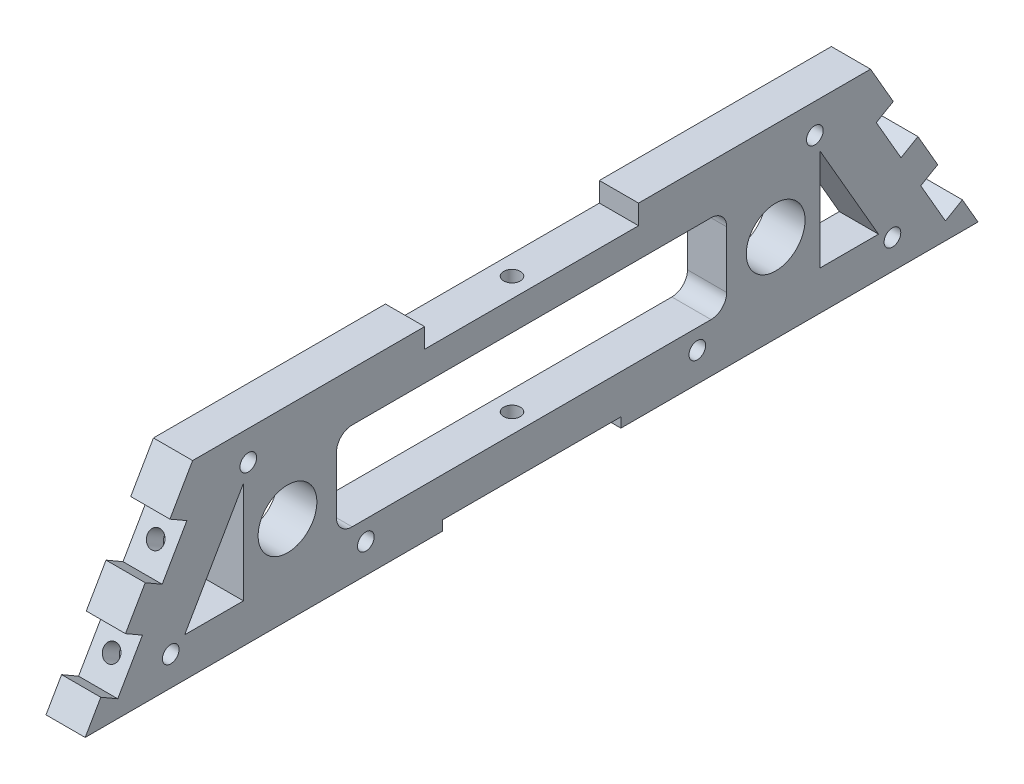
SolidWorks part; units mm, degrees
material "6061-T6 (SS)"
ref_plane "Front Plane" through (0, 0, 0) normal (0, 0, 1) x (1, 0, 0)
ref_plane "Top Plane" through (0, 0, 0) normal (0, 1, 0) x (1, 0, 0)
ref_plane "Right Plane" through (0, 0, 0) normal (1, 0, 0) x (0, 0, -1)
sketch "Sketch1" plane through (0, 0, 0) normal (1, 0, 0) x (0, 0, -1)
  line L0 (0, 0) -> (-17.4143, 30.1625)
  line L1 (-57.8739, 1.5875) -> (-86.8299, 1.5875)
  line L3 (-55.0164, 26.9875) -> (-89.6874, 26.9875)
  line L4 (-127.2895, 30.1625) -> (-89.6874, 30.1625)
  line L5 (-144.7038, 0) -> (-127.2895, 30.1625)
  line L6 (-17.4143, 30.1625) -> (-55.0164, 30.1625)
  line L7 (-55.0164, 30.1625) -> (-55.0164, 26.9875)
  line L8 (-89.6874, 30.1625) -> (-89.6874, 26.9875)
  line L9 (0, 0) -> (-57.8739, 0)
  line L10 (-57.8739, 0) -> (-57.8739, 1.5875)
  line L12 (-144.7038, 0) -> (-86.8299, 0)
  line L13 (-86.8299, 0) -> (-86.8299, 1.5875)
  circle A0 centre (-111.9124, 14.2875) radius 4.7625
  circle A1 centre (-32.7914, 14.2875) radius 4.7625
  dimension "D3" = 9.525
  dimension "D5" = 9.525
  dimension "D9" = 60
  dimension "D12" = 22.225
  dimension "D6" = 79.121
  dimension "D7" = 12.7
  dimension "D11" = 14.2875
  dimension "D14" = 22.225
  dimension "D15" = 15.875
  dimension "D19" = 32.7914
  dimension "D2" = 14.2875
  dimension "D4" = 12.7
  dimension "D8" = 12.7
  dimension "D10" = 60
  dimension "D13" = 15.875
  dimension "D16" = 25.0825
  dimension "D17" = 25.0825
  dimension "D18" = 32.7914
extrude "Boss-Extrude1" add sketch "Sketch1" along normal blind 6.35
hole_wizard "Tap Drill for #6-32 Tap2" positions "Sketch15" profile "Sketch14" hole size "#6-32" standard "ANSI Inch"
sketch "Sketch15" plane through (0, 62.6586, 108.5278) normal (0, 0.5, 0.866) x (1, 0, 0)
  line L5 (6.35, -37.5232) -> (0, -37.5232) construction
  point P3 (3.175, -62.9232)
  point P16 (3.175, -48.6357)
  dimension "D1" = 25.4
  dimension "D2" = 11.1125
sketch "Sketch14" plane through (3.175, 8.1655, 139.9895) normal (1, 0, 0) x (0, -0.866, 0.5)
  line L0 (0, 0) -> (0, 7.1627)
  line L1 (0, 7.1627) -> (1.3525, 6.35)
  line L2 (1.3525, 6.35) -> (1.3525, 0)
  line L5 (1.3525, 0) -> (0, 0)
  line L10 (0, 7.1627) -> (-1.3525, 6.35) construction
  line L11 (0, -6.35) -> (0, 107.95) construction
  dimension "Hole Dia." = 2.7051
  dimension "Hole Depth" = 6.35
  dimension "Drill Angle" = 118
sketch "Sketch18" plane through (0, 0, 0) normal (-1, 0, 0) x (0, 0, 1)
  line L0 (16.1226, 6.35) -> (25.6476, 6.35)
  line L1 (40.7289, 22.225) -> (103.9749, 22.225)
  line L2 (40.7289, 22.225) -> (40.7289, 7.9375)
  line L3 (40.7289, 7.9375) -> (103.9749, 7.9375)
  line L4 (103.9749, 22.225) -> (103.9749, 7.9375)
  line L5 (25.6476, 6.35) -> (25.6476, 22.8478)
  line L6 (127.2895, 30.1625) -> (89.6874, 30.1625) construction
  line L7 (16.1226, 6.35) -> (25.6476, 22.8478)
  line L8 (0, 0) -> (57.8739, 0) construction
  line L10 (0, 0) -> (17.4143, 30.1625) construction
  line L11 (72.3519, 26.9875) -> (72.3519, -9.7243) construction
  line L12 (55.0164, 26.9875) -> (89.6874, 26.9875) construction
  line L13 (119.0562, 6.35) -> (119.0562, 22.8478)
  line L14 (128.5812, 6.35) -> (119.0562, 22.8478)
  line L15 (128.5812, 6.35) -> (119.0562, 6.35)
  circle A0 centre (32.7914, 14.2875) radius 4.7625 construction
  circle A2 centre (111.9124, 14.2875) radius 4.7625 construction
  circle A3 centre (32.7914, 14.2875) radius 4.7625 construction
  dimension "D2" = 7.9375
  dimension "D1" = 7.9375
  dimension "D3" = 7.9375
  dimension "D4" = 22.225
  dimension "D5" = 7.1437
  dimension "D6" = 6.35
  dimension "D7" = 9.525
extrude "Cut-Extrude1" cut sketch "Sketch18" against normal through all
fillet "Fillet1" radius 2.54 4 edges at (3.175, 7.9375, 40.7289) (3.175, 22.225, 40.7289) (3.175, 7.9375, 103.9749) (3.175, 22.225, 103.9749)
hole_wizard "Tap Drill for #6-32 Tap4" positions "Sketch22" profile "Sketch21" hole size "#6-32" standard "ANSI Inch" end condition through all
sketch "Sketch22" plane through (0, 26.9875, 0) normal (0, 1, 0) x (1, 0, 0)
  line L0 (6.35, -55.0164) -> (6.35, -89.6874) construction
  line L1 (6.35, -89.6874) -> (0, -89.6874) construction
  point P0 (3.175, -72.3519)
  point P4 (6.35, -72.3519)
  point P7 (3.175, -89.6874)
sketch "Sketch21" plane through (3.175, 26.9875, 72.3519) normal (1, 0, 0) x (0, 0, 1)
  line L0 (0, 0) -> (0, 26.9875)
  line L1 (0, 26.9875) -> (1.3525, 26.9875)
  line L2 (1.3525, 26.9875) -> (1.3525, 0)
  line L5 (1.3525, 0) -> (0, 0)
  line L11 (0, -6.35) -> (0, 107.95) construction
  dimension "Thru Hole Dia." = 2.7051
  dimension "Thru Hole Depth" = 26.9875
ref_plane "Plane1" through (0, 0, 72.3519) normal (0, 0, -1) x (-1, 0, 0)
mirror "Mirror1" about plane through (0, 0, 72.3519) normal (0, 0, -1) of "Tap Drill for #6-32 Tap2"
hole_wizard "Tap Drill for #6-32 Tap1" positions "Sketch13" profile "Sketch12" hole size "#6-32" standard "ANSI Inch"
sketch "Sketch13" plane through (6.35, 15.8955, 9.3658) normal (1, 0, 0) x (0, 0, -1)
  circle A0 centre (-102.5466, -1.608) radius 4.7625 construction
  circle A1 centre (-102.5466, -1.608) radius 4.7625 construction
  point P24 (-108.8966, 9.5045)
  point P58 (-89.8466, -11.133)
  point P62 (-121.4696, -11.133)
  dimension "D1" = 11.1125
  dimension "D4" = 6.35
  dimension "D7" = 12.7
  dimension "D8" = 9.525
  dimension "D9" = 18.923
  dimension "D10" = 9.525
sketch "Sketch12" plane through (6.35, 25.4, 118.2624) normal (0, 1, 0) x (0, 0, -1)
  line L0 (0, 0) -> (0, 7.1627)
  line L1 (0, 7.1627) -> (1.3525, 6.35)
  line L2 (1.3525, 6.35) -> (1.3525, 0)
  line L5 (1.3525, 0) -> (0, 0)
  line L10 (0, 7.1627) -> (-1.3525, 6.35) construction
  line L11 (0, -6.35) -> (0, 107.95) construction
  dimension "Hole Dia." = 2.7051
  dimension "Hole Depth" = 6.35
  dimension "Drill Angle" = 118
mirror "Mirror2" about plane through (0, 0, 72.3519) normal (0, 0, -1) of "Tap Drill for #6-32 Tap1"
sketch "Sketch23" plane through (0, 0, 0) normal (0, 0.5, -0.866) x (-1, 0, 0)
  line L0 (-6.35, 0) -> (-6.35, 5.0578) construction
  line L1 (-6.35, 27.4606) -> (0, 27.4606)
  line L2 (-6.35, 27.4606) -> (-6.35, 19.4596)
  line L3 (-6.35, 19.4596) -> (0, 19.4596)
  line L4 (0, 27.4606) -> (0, 19.4596)
  line L5 (0, 0) -> (0, 5.0578) construction
  line L7 (0, 13.0588) -> (-6.35, 13.0588)
  line L8 (0, 13.0588) -> (0, 5.0578)
  line L9 (0, 5.0578) -> (-6.35, 5.0578)
  line L10 (-6.35, 13.0588) -> (-6.35, 5.0578)
  line L16 (-6.1722, 27.4606) -> (-6.1722, 32.2231)
  line L17 (-6.1722, 32.2231) -> (-23.9522, 32.2231)
  line L18 (-23.9522, 32.2231) -> (-23.9522, 27.4606)
  line L19 (-23.9522, 27.4606) -> (-30.48, 27.4606)
  line L20 (-30.48, 27.4606) -> (-30.48, 19.5231)
  line L21 (-30.48, 19.5231) -> (-23.9522, 19.5231)
  line L22 (-23.9522, 19.5231) -> (-23.9522, 12.9953)
  line L23 (-23.9522, 12.9953) -> (-30.48, 12.9953)
  line L24 (-30.48, 12.9953) -> (-30.48, 5.0578)
  line L25 (-30.48, 5.0578) -> (0.1778, 5.0578)
  line L26 (0.1778, 5.0578) -> (0.1778, 12.9953)
  line L27 (0.1778, 12.9953) -> (-6.1722, 12.9953)
  line L28 (-6.1722, 12.9953) -> (-6.1722, 19.5231)
  line L29 (-6.1722, 19.5231) -> (0.1778, 19.5231)
  line L30 (0.1778, 19.5231) -> (0.1778, 27.4606)
  line L31 (0.1778, 27.4606) -> (-6.1722, 27.4606)
  line L32 (-6.1722, 27.4606) -> (-6.1722, 32.2231) construction
  line L33 (-6.1722, 32.2231) -> (-23.9522, 32.2231) construction
  line L34 (-23.9522, 32.2231) -> (-23.9522, 27.4606) construction
  line L35 (-23.9522, 27.4606) -> (-30.48, 27.4606) construction
  line L36 (-30.48, 27.4606) -> (-30.48, 19.5231) construction
  line L37 (-30.48, 19.5231) -> (-23.9522, 19.5231) construction
  line L38 (-23.9522, 19.5231) -> (-23.9522, 12.9953) construction
  line L39 (-23.9522, 12.9953) -> (-30.48, 12.9953) construction
  line L40 (-30.48, 12.9953) -> (-30.48, 5.0578) construction
  line L41 (-30.48, 5.0578) -> (0.1778, 5.0578) construction
  line L42 (0.1778, 5.0578) -> (0.1778, 12.9953) construction
  line L43 (0.1778, 12.9953) -> (-6.1722, 12.9953) construction
  line L44 (-6.1722, 12.9953) -> (-6.1722, 19.5231) construction
  line L45 (-6.1722, 19.5231) -> (0.1778, 19.5231) construction
  line L46 (0.1778, 19.5231) -> (0.1778, 27.4606) construction
  line L47 (0.1778, 27.4606) -> (-6.1722, 27.4606) construction
  dimension "D2" = 8.001
  dimension "D3" = 8.001
  dimension "D1" = 0
extrude "Cut-Extrude2" cut sketch "Sketch23" against normal blind 3.175
mirror "Mirror3" about plane through (0, 0, 72.3519) normal (0, 0, -1) of "Cut-Extrude2"
equation "\"D8@Sketch1\"=\"D4@Sketch1\""
equation "\"D17@Sketch1\"=\"D16@Sketch1\""
equation "\"D14@Sketch1\"=\"D12@Sketch1\""
equation "\"D15@Sketch1\"=\"D13@Sketch1\""
